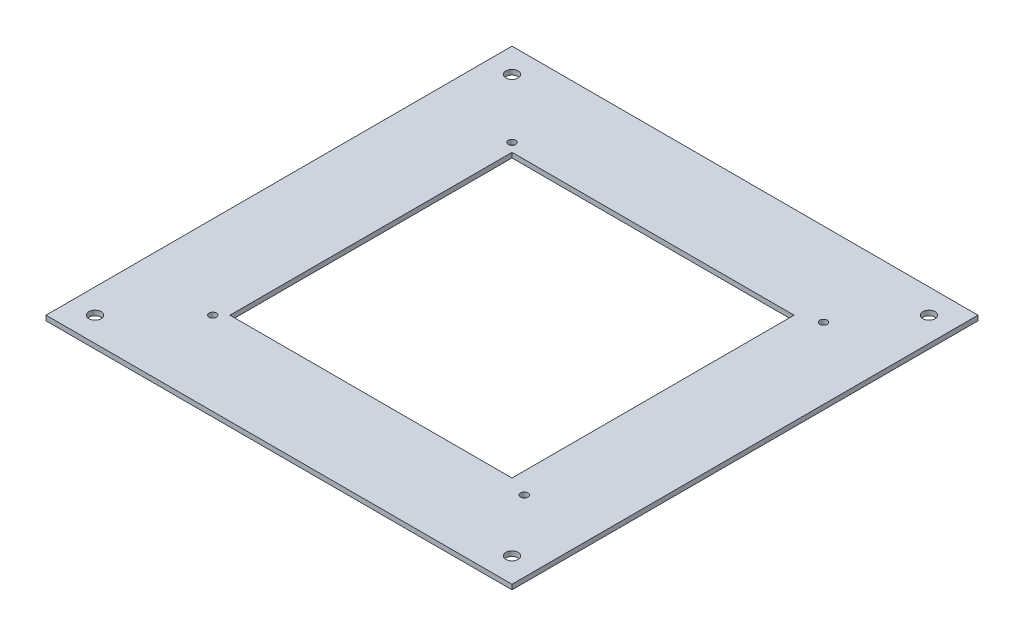
SolidWorks part; units mm, degrees
ref_plane "Alzado" through (0, 0, 0) normal (0, 0, 1) x (1, 0, 0)
ref_plane "Planta" through (0, 0, 0) normal (0, 1, 0) x (1, 0, 0)
ref_plane "Vista lateral" through (0, 0, 0) normal (1, 0, 0) x (0, 0, -1)
sketch "Croquis1" plane through (0, 0, 0) normal (0, 1, 0) x (1, 0, 0)
  line L0 (-95, 95) -> (95, 95)
  line L1 (-85, -85) -> (85, -85) construction
  line L2 (-85, -85) -> (-85, 85) construction
  line L3 (-85, 85) -> (85, 85) construction
  line L4 (85, -85) -> (85, 85) construction
  line L5 (-85, -85) -> (85, 85) construction
  line L6 (-85, 85) -> (85, -85) construction
  line L7 (95, -95) -> (95, 95)
  line L8 (-95, -95) -> (95, -95)
  line L9 (-95, -95) -> (-95, 95)
  line L10 (-61, 0) -> (-61, -61) construction
  line L11 (0, 0) -> (-61, 0) construction
  line L12 (0, 0) -> (0, 61) construction
  line L13 (0, 61) -> (-61, 61) construction
  line L14 (-61, 0) -> (-61, 61) construction
  line L15 (0, 0) -> (66, 0)
  line L16 (0, 0) -> (0, 61)
  line L17 (0, 61) -> (66, 61) construction
  line L18 (66, 0) -> (66, 61) construction
  line L19 (-61, -61) -> (66, -61) construction
  line L20 (66, -61) -> (66, 0) construction
  line L22 (-57.5, -57.5) -> (57.5, -57.5)
  line L23 (-57.5, -57.5) -> (-57.5, 57.5)
  line L24 (-57.5, 57.5) -> (57.5, 57.5)
  line L25 (57.5, -57.5) -> (57.5, 57.5)
  line L26 (-57.5, -57.5) -> (57.5, 57.5) construction
  line L27 (-57.5, 57.5) -> (57.5, -57.5) construction
  circle A0 centre (-85, 85) radius 2.5
  circle A1 centre (85, 85) radius 2.5
  circle A2 centre (85, -85) radius 2.5
  circle A3 centre (-85, -85) radius 2.5
  circle A4 centre (-61, 61) radius 1.5
  circle A5 centre (66, 61) radius 1.5
  circle A6 centre (66, -61) radius 1.5
  circle A7 centre (-61, -61) radius 1.5
  point P0 (0, 0)
  dimension "D3" = 5
  dimension "D6" = 3
  dimension "D1" = 170
  dimension "D2" = 10
  dimension "D4" = 61
  dimension "D5" = 66
  dimension "D7" = 115
extrude "Saliente-Extruir1" add sketch "Croquis1" along normal blind 2
